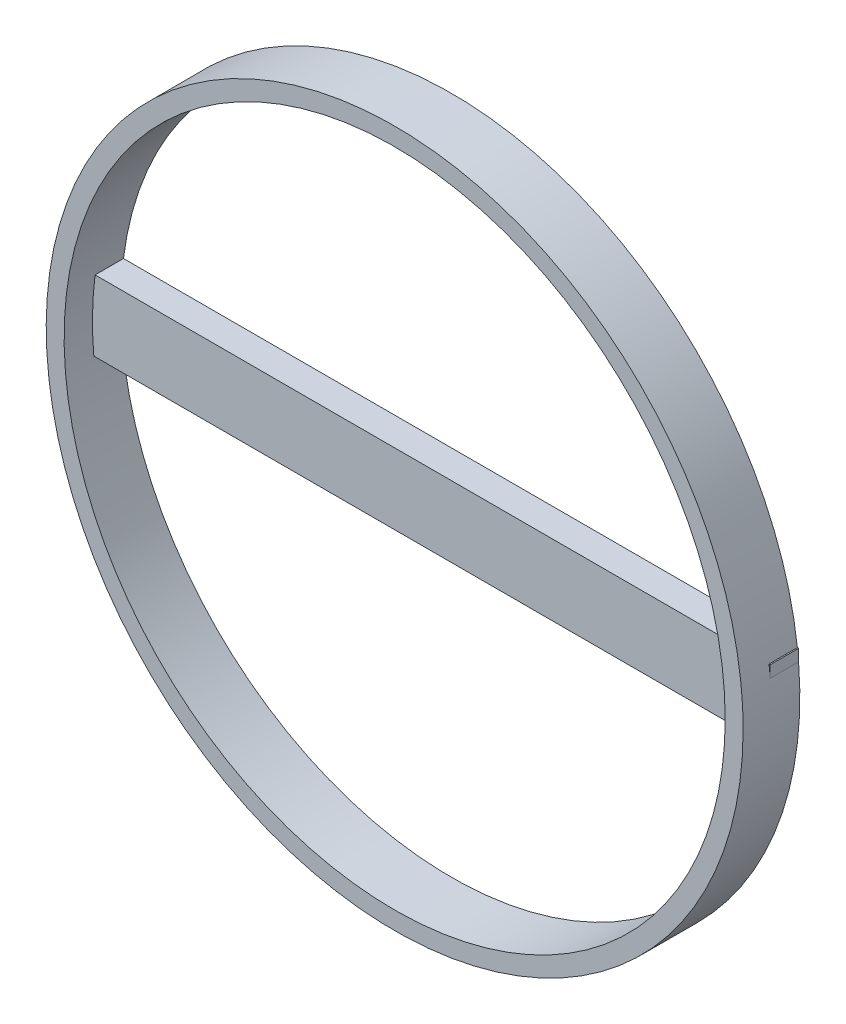
SolidWorks part; units mm, degrees
ref_plane "Front Plane" through (0, 0, 0) normal (0, 0, 1) x (1, 0, 0)
ref_plane "Top Plane" through (0, 0, 0) normal (0, 1, 0) x (1, 0, 0)
ref_plane "Right Plane" through (0, 0, 0) normal (1, 0, 0) x (0, 0, -1)
sketch "Sketch1" plane through (0, 0, 0) normal (0, 0, 1) x (1, 0, 0)
  circle A0 centre (0, 0) radius 23.3023
  circle A1 centre (0, 0) radius 24.565
extrude "Boss-Extrude1" add sketch "Sketch1" along normal blind 4
sketch "Sketch2" plane through (0, 0, 0) normal (0, 0, 1) x (1, 0, 0)
  line L6 (-24.3914, 2.9154) -> (24.4764, 2.9154)
  line L7 (-24.3914, 2.9154) -> (-24.3914, -2.0846)
  line L8 (-24.3914, -2.0846) -> (24.4764, -2.0846)
  line L9 (24.4764, 2.9154) -> (24.4764, -2.0846)
  circle A0 centre (0, 0) radius 24.565 construction
  dimension "D1" = 5
extrude "Boss-Extrude6" add sketch "Sketch2" along normal blind 2 contours L6 L9 L8 L7
ref_plane "Plane5" through (-23.1192, 2.9154, 2) normal (1, 0, 0) x (0, 0, -1)
